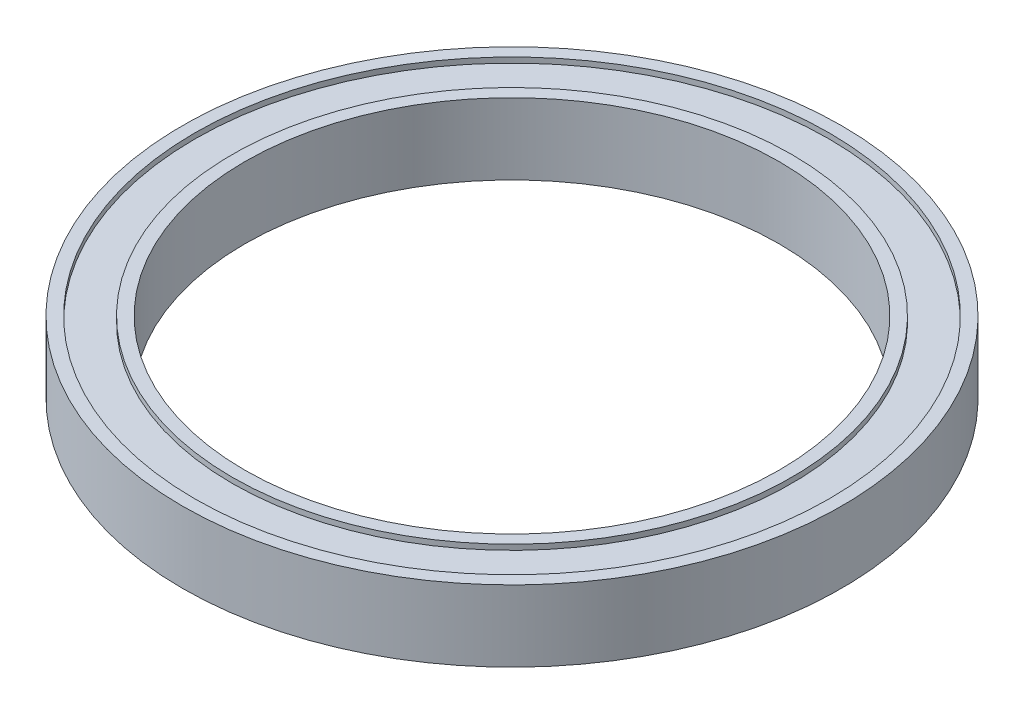
SolidWorks part; units mm, degrees
material "6061 合金"
ref_plane "前视基准面" through (0, 0, 0) normal (0, 0, 1) x (1, 0, 0)
ref_plane "上视基准面" through (0, 0, 0) normal (0, 1, 0) x (1, 0, 0)
ref_plane "右视基准面" through (0, 0, 0) normal (1, 0, 0) x (0, 0, -1)
sketch "草图1" plane through (0, 0, 0) normal (0, 1, 0) x (1, 0, 0)
  circle A0 centre (0, 0) radius 18.5
  circle A1 centre (0, 0) radius 15
  dimension "D1" = 37
  dimension "D2" = 30
extrude "凸台-拉伸1" add sketch "草图1" along normal blind 4
sketch "草图2" plane through (0, 4, 0) normal (0, 1, 0) x (1, 0, 0)
  circle A0 centre (0, 0) radius 17.8
  circle A1 centre (0, 0) radius 15.7
  circle A2 centre (0, 0) radius 18.5 construction
  circle A3 centre (0, 0) radius 15 construction
  dimension "D1" = 0.7
  dimension "D2" = 0.7
extrude "切除-拉伸1" cut sketch "草图2" against normal blind 0.3
ref_plane "基准面4" through (0, 2, 0) normal (0, 1, 0) x (1, 0, 0)
mirror "镜向1" about plane through (0, 2, 0) normal (0, 1, 0) of "切除-拉伸1"
